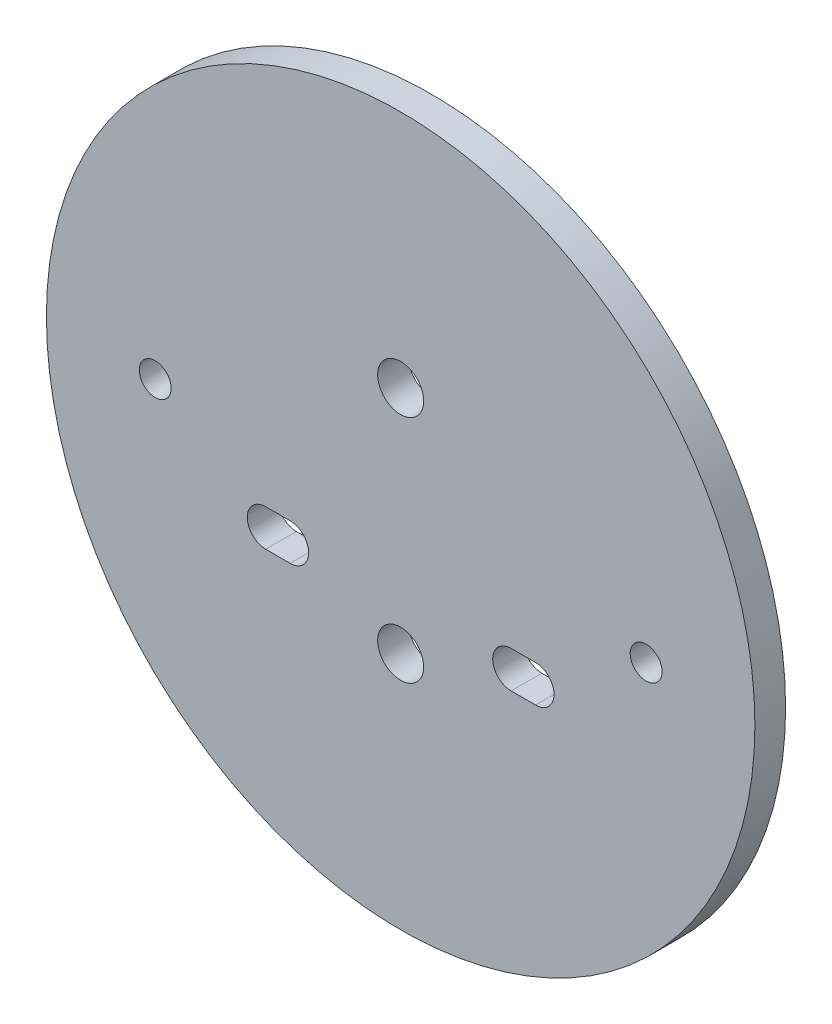
SolidWorks part; units mm, degrees
material "Balsa"
ref_plane "Front" through (0, 0, 0) normal (0, 0, 1) x (1, 0, 0)
ref_plane "Top" through (0, 0, 0) normal (0, 1, 0) x (1, 0, 0)
ref_plane "Right" through (0, 0, 0) normal (1, 0, 0) x (0, 0, -1)
sketch "Sketch2" plane through (0, 0, 0) normal (0, 0, 1) x (1, 0, 0)
  line L0 (-56.2467, 0) -> (91.426, 0) construction
  line L1 (0, 58.7371) -> (0, -82.5124) construction
  circle A0 centre (0, 0) radius 73.3171
  circle A1 centre (-50.8, 0) radius 3.302
  circle A2 centre (50.8, 0) radius 3.302
  circle A3 centre (0, 23.8125) radius 4.7625
  circle A4 centre (0, -23.8125) radius 4.7625
  dimension "D1" = 146.6342
  dimension "D2" = 47.625
  dimension "D4" = 9.525
  dimension "D5" = 101.6
  dimension "D6" = 6.604
  dimension "D3" = 23.8125
  dimension "D7" = 50.8
extrude "Boss-Extrude1" add sketch "Sketch2" along normal mid plane 6.35
sketch "Sketch3" plane through (0, 0, -3.175) normal (0, 0, -1) x (-1, 0, 0)
  line L0 (-27.94, -15.24) -> (-22.86, -15.24) construction
  line L1 (-27.94, -11.43) -> (-22.86, -11.43)
  line L2 (-27.94, -19.05) -> (-22.86, -19.05)
  arc A2 (-27.94, -11.43) -> (-27.94, -19.05) centre (-27.94, -15.24) ccw
  arc A11 (-22.86, -19.05) -> (-22.86, -11.43) centre (-22.86, -15.24) ccw
  point P4 (-25.4, -15.24)
  dimension "D3" = 5.08
  dimension "D4" = 15.24
  dimension "D5" = 22.86
  dimension "D6" = 3.81
extrude "Cut-Extrude1" cut sketch "Sketch3" against normal blind 6.35
mirror "Mirror1" about plane through (0, 0, 0) normal (1, 0, 0) of "Cut-Extrude1"
